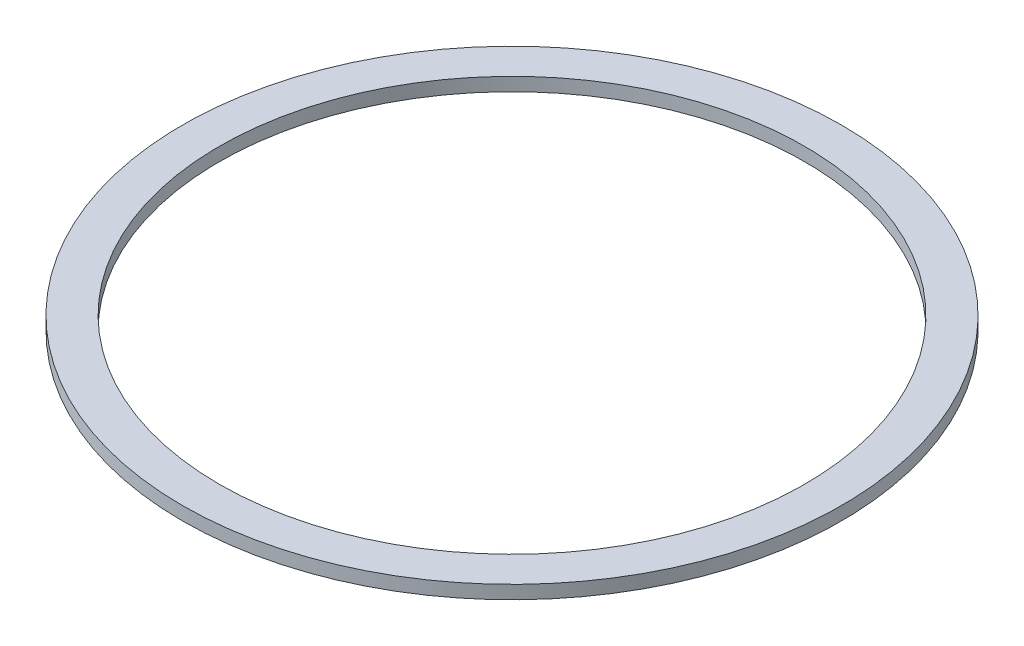
SolidWorks part; units mm, degrees
material "Chrome Stainless Steel"
ref_plane "Front Plane" through (0, 0, 0) normal (0, 0, 1) x (1, 0, 0)
ref_plane "Top Plane" through (0, 0, 0) normal (0, 1, 0) x (1, 0, 0)
ref_plane "Right Plane" through (0, 0, 0) normal (1, 0, 0) x (0, 0, -1)
sketch "Sketch1" plane through (0, 0, 0) normal (0, 1, 0) x (1, 0, 0)
  circle A0 centre (0, 0) radius 69.596
  circle A1 centre (0, 0) radius 78.359
  dimension "D1" = 139.192
  dimension "D2" = 156.718
extrude "Boss-Extrude1" add sketch "Sketch1" along normal blind 3.175
